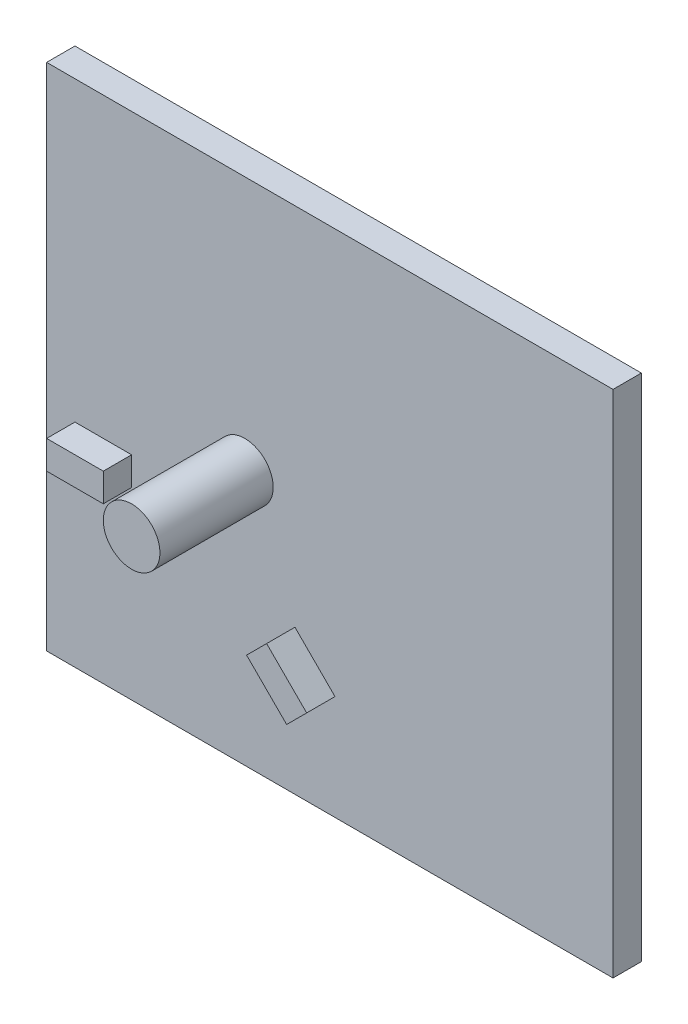
SolidWorks part; units mm, degrees
material "PE haute densité"
ref_plane "Plan de face" through (0, 0, 0) normal (0, 0, 1) x (1, 0, 0)
ref_plane "Plan de dessus" through (0, 0, 0) normal (0, 1, 0) x (1, 0, 0)
ref_plane "Plan de droite" through (0, 0, 0) normal (1, 0, 0) x (0, 0, -1)
sketch "Esquisse1" plane through (0, 0, 0) normal (0, 0, 1) x (1, 0, 0)
  line L1 (100, 90) -> (-100, 90)
  line L2 (100, 90) -> (100, -90)
  line L3 (100, -90) -> (-100, -90)
  line L4 (-100, 90) -> (-100, -90)
  line L5 (100, 90) -> (-100, -90) construction
  line L6 (100, -90) -> (-100, 90) construction
  circle A0 centre (-30, 0) radius 10
  dimension "D1" = 20
  dimension "D2" = 200
  dimension "D3" = 180
  dimension "D4" = 30
extrude "Boss.-Extru.1" add sketch "Esquisse1" along normal blind 10
sketch "Esquisse3" plane through (0, 0, 0) normal (0, 0, -1) x (-1, 0, 0)
  circle A1 centre (30, 0) radius 10
extrude "Boss.-Extru.2" add sketch "Esquisse3" against normal blind 50
sketch "Esquisse4" plane through (0, 0, 10) normal (0, 0, 1) x (1, 0, 0)
  line L1 (-70, -25) -> (-90, -25)
  line L2 (-70, -25) -> (-70, -15)
  line L3 (-70, -15) -> (-90, -15)
  line L4 (-90, -25) -> (-90, -15)
  line L5 (-70, -25) -> (-90, -15) construction
  line L6 (-70, -15) -> (-90, -25) construction
  line L7 (-12.3223, -38.8909) -> (1.8198, -53.033)
  line L8 (-12.3223, -38.8909) -> (-19.3934, -45.9619)
  line L9 (1.8198, -53.033) -> (-5.2513, -60.1041)
  line L10 (-19.3934, -45.9619) -> (-5.2513, -60.1041)
  circle A0 centre (-30, 0) radius 10 construction
  point P0 (-80, -20)
  dimension "D1" = 15
  dimension "D2" = 20
  dimension "D3" = 10
  dimension "D4" = 40
  dimension "D5" = 20
  dimension "D6" = 10
  dimension "D7" = 45
  dimension "D8" = 15
  dimension "D9" = 40
extrude "Boss.-Extru.3" add sketch "Esquisse4" along normal blind 10
